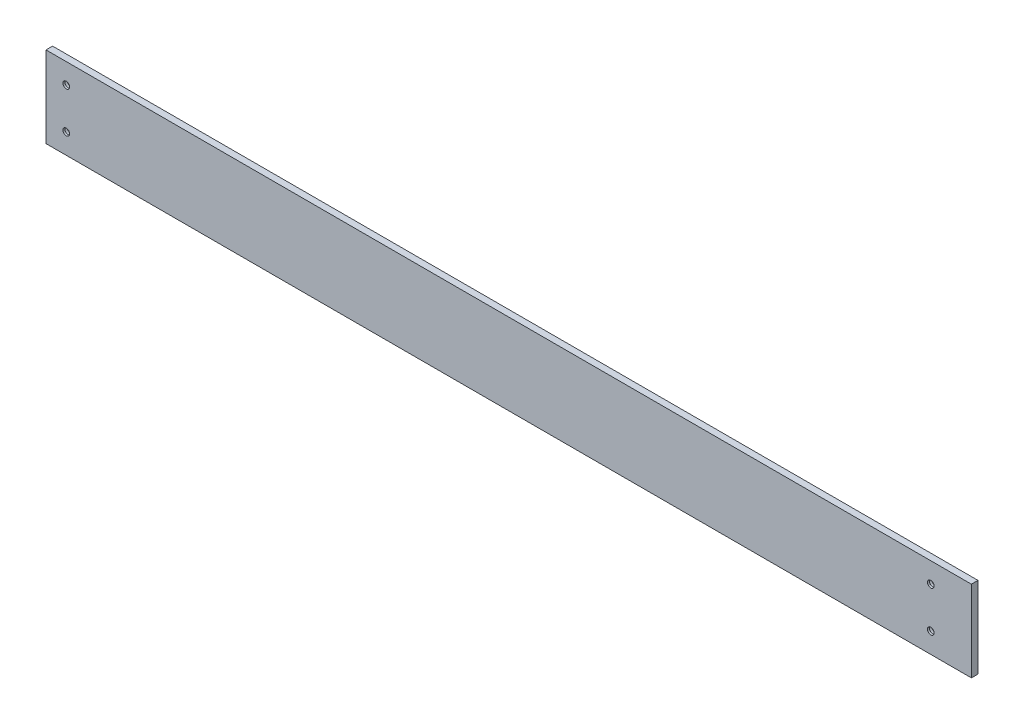
SolidWorks part; units mm, degrees
ref_plane "Plan de face" through (0, 0, 0) normal (0, 0, 1) x (1, 0, 0)
ref_plane "Plan de dessus" through (0, 0, 0) normal (0, 1, 0) x (1, 0, 0)
ref_plane "Plan de droite" through (0, 0, 0) normal (1, 0, 0) x (0, 0, -1)
sketch "Esquisse1" plane through (0, 0, 0) normal (0, 0, 1) x (1, 0, 0)
  line L1 (-456, -40) -> (456, -40)
  line L2 (-456, -40) -> (-456, 40)
  line L3 (-456, 40) -> (456, 40)
  line L4 (456, -40) -> (456, 40)
  line L5 (-456, -40) -> (456, 40) construction
  line L6 (-456, 40) -> (456, -40) construction
  point P0 (0, 0)
  dimension "D1" = 80
  dimension "D2" = 912
extrude "Boss.-Extru.1" add sketch "Esquisse1" along normal blind 6.5
hole_wizard "Dégagement M61" positions "Esquisse3" profile "Esquisse2" hole size "M6" standard "JIS" end condition through all
sketch "Esquisse3" plane through (0, 0, 6.5) normal (0, 0, 1) x (1, 0, 0)
  point P0 (-436, 20)
  point P2 (-436, -20)
sketch "Esquisse2" plane through (-436, 20, 6.5) normal (1, 0, 0) x (0, -1, 0)
  line L0 (0, 0) -> (0, 6.5)
  line L1 (0, 6.5) -> (3.3, 6.5)
  line L2 (3.3, 6.5) -> (3.3, 0)
  line L5 (3.3, 0) -> (0, 0)
  line L11 (0, -6.35) -> (0, 107.95) construction
  dimension "Diamètre du perçage jusqu'au prochain" = 6.6
  dimension "Profondeur du perçage jusqu'au prochain" = 6.5
hole_wizard "Chambrage pour vis à tête ronde bombée M61" positions "Esquisse5" profile "Esquisse4" counterbore size "M6" standard "Ansi Metric" end condition through all
sketch "Esquisse5" plane through (0, 0, 0) normal (0, 0, -1) x (-1, 0, 0)
  point P0 (436, 20)
  point P2 (436, -20)
sketch "Esquisse4" plane through (-436, 20, 0) normal (1, 0, 0) x (0, 1, 0)
  line L0 (0, 0) -> (0, 6.5)
  line L1 (0, 6.5) -> (3.3, 6.5)
  line L2 (3.3, 4.625) -> (3.3, 6.5)
  line L3 (3.3, 4.625) -> (3.325, 4.6)
  line L4 (3.325, 4.6) -> (6.5, 4.6)
  line L5 (6.5, 4.6) -> (6.5, 0)
  line L7 (0, 0) -> (6.5, 0)
  line L9 (-3.3, 4.625) -> (-3.325, 4.6) construction
  line L11 (0, -6.35) -> (0, 107.95) construction
  dimension "Diamètre du perçage jusqu'au prochain" = 6.6
  dimension "Profondeur du perçage jusqu'au prochain" = 6.5
  dimension "Diamètre du chambrage" = 13
  dimension "Profondeur du chambrage" = 4.6
  dimension "Diamètre du fraisage milieu" = 6.65
  dimension "Angle du fraisage milieu" = 90
pattern_linear "Répétition linéaire1" count 2 spacing 852 along (1, 0, 0) of "Chambrage pour vis à tête ronde bombée M61"
